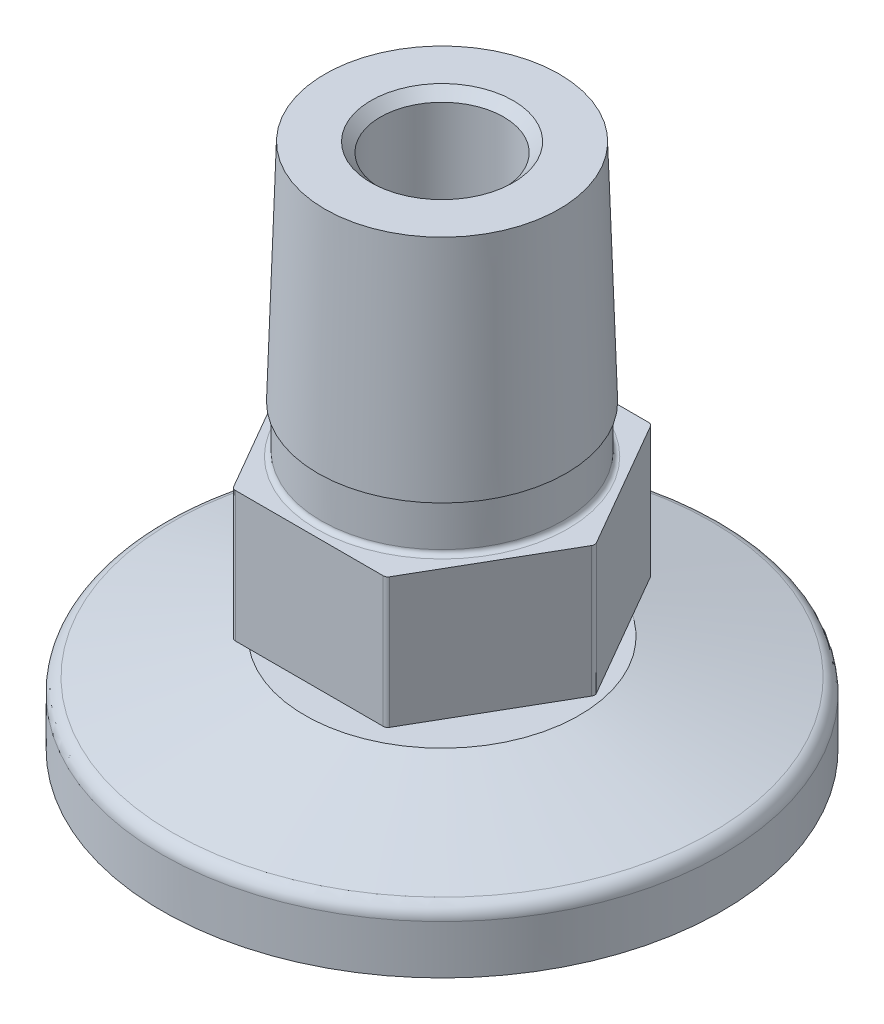
SolidWorks part; units mm, degrees
material "AISI 316 Annealed Stainless Steel Bar (SS)"
ref_plane "Front Plane" through (0, 0, 0) normal (0, 0, 1) x (1, 0, 0)
ref_plane "Top Plane" through (0, 0, 0) normal (0, 1, 0) x (1, 0, 0)
ref_plane "Right Plane" through (0, 0, 0) normal (1, 0, 0) x (0, 0, -1)
sketch "Sketch1" plane through (0, 0, 0) normal (1, 0, 0) x (0, 0, -1)
  line L0 (0, 0) -> (0, 5.25) construction
  line L1 (-15, 0) -> (-15, 3.2)
  line L2 (-15, 3.2) -> (-7.3493, 5.25)
  line L6 (0, 2.5) -> (-8.1, 2.5)
  line L7 (-8.1, 2.5) -> (-8.1, 0)
  line L8 (-8.1, 0) -> (-15, 0)
  line L9 (-7.3493, 5.25) -> (0, 5.25)
  line L10 (0, 5.25) -> (0, 2.5)
  dimension "D1" = 75
  dimension "D2" = 14.6986
  dimension "Flange ID" = 16.2
  dimension "Flange OD" = 30
  dimension "D5" = 3.2
  dimension "Flange Height" = 5.25
  dimension "D9" = 2.5
revolve "Flange" add sketch "Sketch1" angle 360 about L0
sketch "Sketch5" plane through (0, 2.5, 0) normal (0, -1, 0) x (1, 0, 0)
  circle A0 centre (0, 0) radius 4.445
  dimension "D1" = 8.89
extrude "Stub" add sketch "Sketch5" against normal offset from surface (4.104 mm away) 6.604 up to face at (0, 0, -8.1)
ref_plane "Plane1" through (0, -1.905, 0) normal (0, -1, 0) x (-1, 0, 0)
sketch "Sketch6" plane through (0, 6.604, 0) normal (0, 1, 0) x (1, 0, 0)
  line L1 (4.1061, 7.112) -> (-4.1061, 7.112)
  line L2 (-4.1061, 7.112) -> (-8.2122, 0)
  line L3 (-8.2122, 0) -> (-4.1061, -7.112)
  line L4 (-4.1061, -7.112) -> (4.1061, -7.112)
  line L5 (4.1061, -7.112) -> (8.2122, 0)
  line L6 (8.2122, 0) -> (4.1061, 7.112)
  circle A0 centre (0, 0) radius 7.112 construction
  dimension "D1" = 14.224
extrude "Hex" add sketch "Sketch6" along normal blind 6.985
sketch "Sketch7" plane through (0, 0, 0) normal (0, 0, 1) x (1, 0, 0)
  line L0 (-6.731, 13.589) -> (-6.2746, 28.194)
  line L1 (-8.2122, 13.589) -> (-4.1061, 13.589) construction
  line L2 (-6.2746, 28.194) -> (0, 28.194)
  line L3 (0, 28.194) -> (0, 13.589)
  line L4 (-4.1061, 13.589) -> (4.1061, 13.589) construction
  line L5 (0, 13.589) -> (-6.731, 13.589)
  line L6 (0, 0) -> (0, 39.0241) construction
  dimension "D1" = 14.605
  dimension "D3" = 13.462
  dimension "D4" = 1.79
revolve "Thread Body" add sketch "Sketch7" angle 360 about L6
cosmetic thread "Cosmetic Thread1"
sketch "Sketch8" plane through (0, 2.5, 0) normal (0, -1, 0) x (1, 0, 0)
  circle A0 centre (0, 0) radius 9.652
  dimension "D1" = 19.304
extrude "Centering Ring Boss" [suppressed] add sketch "Sketch8" along normal up to surface (2.5 mm away)
sketch "Sketch9" [suppressed] plane through (0, 0, 0) normal (0, 0, 1) x (1, 0, 0)
  line L0 (-6.477, 35.306) -> (-6.0327, 49.53)
  line L1 (-6.0327, 49.53) -> (0, 49.53)
  line L2 (0, 49.53) -> (0, 35.306)
  line L3 (6.477, 35.306) -> (-6.477, 35.306) construction
  line L4 (0, 35.306) -> (-6.477, 35.306)
  line L5 (0, 0) -> (0, 39.9227) construction
  dimension "D1" = 1.789
  dimension "D2" = 19.05
revolve "ThreadBody" add sketch "Sketch9" angle 360 about L5
cosmetic thread "Cosmetic Thread2" [suppressed]
sketch "Sketch11" plane through (0, 0, 0) normal (0, 0, 1) x (1, 0, 0)
  line L0 (-21.717, 13.589) -> (-21.717, 16.129)
  line L1 (-21.717, 16.129) -> (-6.477, 16.129)
  line L2 (-6.477, 16.129) -> (-6.477, 13.589)
  line L3 (-6.477, 13.589) -> (-21.717, 13.589)
  line L4 (0, 0) -> (0, 108.0919) construction
  line L5 (-15, 0) -> (15, 0) construction
  dimension "D1" = 2.54
  dimension "D2" = 12.954
  dimension "D3" = 15.24
  dimension "1.37" = 13.589
revolve "Cut-Revolve1" cut sketch "Sketch11" angle 360 about L4
sketch "Sketch10" [suppressed] plane through (0, 5.25, 0) normal (0, 1, 0) x (1, 0, 0)
  line L1 (6.3791, 11.049) -> (-6.3791, 11.049)
  line L2 (-6.3791, 11.049) -> (-12.7583, 0)
  line L3 (-12.7583, 0) -> (-6.3791, -11.049)
  line L4 (-6.3791, -11.049) -> (6.3791, -11.049)
  line L5 (6.3791, -11.049) -> (12.7583, 0)
  line L6 (12.7583, 0) -> (6.3791, 11.049)
  circle A0 centre (0, 0) radius 11.049 construction
  dimension "D1" = 22.098
extrude "Hex Body" [suppressed] add sketch "Sketch10" along normal up to surface (30.056 mm away)
sketch "Sketch3" plane through (0, 0, 0) normal (0, 1, 0) x (1, 0, 0)
  circle A0 centre (0, 0) radius 3.302
  dimension "Bore Dia" = 6.604
extrude "Center Bore" cut sketch "Sketch3" along normal through all
sketch "Sketch12" [suppressed] plane through (0, 0, 0) normal (0, 0, 1) x (1, 0, 0)
  line L0 (-5.334, 25.4) -> (-5.334, 5.25) construction
  line L1 (-5.334, 19.812) -> (-4.7625, 19.812)
  line L2 (-5.334, 19.812) -> (-5.334, 10.414)
  line L3 (-5.334, 10.414) -> (-4.7625, 10.414)
  line L4 (-4.7625, 19.812) -> (-4.7625, 10.414)
  line L5 (0, 0) -> (0, 21.9573) construction
  line L6 (5.334, 25.4) -> (-5.334, 25.4) construction
  line L7 (4.7625, 19.812) -> (4.7625, 10.414)
  line L8 (5.334, 10.414) -> (4.7625, 10.414)
  line L9 (5.334, 19.812) -> (5.334, 10.414)
  line L10 (5.334, 19.812) -> (4.7625, 19.812)
  dimension "D1" = 9.398
  dimension "D2" = 5.588
  dimension "D3" = 9.525
extrude "Grip Face" [suppressed] cut sketch "Sketch12" against normal through all both and the other way through all
sketch "Sketch13" [suppressed] plane through (0, 0, 0) normal (0, 0, 1) x (1, 0, 0)
  line L0 (15.875, 7.62) -> (20.955, 11.811)
  line L1 (20.955, 11.811) -> (20.955, 28.575)
  line L2 (0, 0) -> (0, 54.9571) construction
  line L3 (20.955, 28.575) -> (14.224, 28.575)
  line L4 (14.224, 2.5) -> (14.224, 49.784) construction
  line L5 (14.224, 28.575) -> (14.224, 7.62)
  line L7 (14.224, 7.62) -> (15.875, 7.62)
  line L8 (15.875, 7.62) -> (-15.875, 7.62) construction
  line L9 (-27.5, 0) -> (27.5, 0) construction
  line L10 (15.875, 6.3149) -> (15.875, 7.62) construction
  dimension "D1" = 41.91
  dimension "D2" = 28.575
  dimension "D3" = 11.811
revolve "Center Body" [suppressed] add sketch "Sketch13" angle 360 about L2
sketch "Sketch14" [suppressed] plane through (0, 0, 0) normal (0, 0, 1) x (1, 0, 0)
  line L0 (-20.955, 28.575) -> (-20.955, 11.811) construction
  line L1 (-20.955, 22.352) -> (-17.399, 22.352)
  line L2 (-20.955, 22.352) -> (-20.955, 7.62)
  line L3 (-20.955, 7.62) -> (-17.399, 7.62)
  line L4 (-17.399, 22.352) -> (-17.399, 7.62)
  line L5 (0, 0) -> (0, 23.4644) construction
  line L6 (-27.5, 0) -> (27.5, 0) construction
  line L7 (15.875, 7.62) -> (-15.875, 7.62) construction
  line L8 (17.399, 22.352) -> (17.399, 7.62)
  line L9 (20.955, 7.62) -> (17.399, 7.62)
  line L10 (20.955, 22.352) -> (20.955, 7.62)
  line L11 (20.955, 22.352) -> (17.399, 22.352)
  dimension "D1" = 34.798
  dimension "D2" = 22.352
extrude "Flat" [suppressed] cut sketch "Sketch14" against normal through all both and the other way through all
sketch "Sketch16" [suppressed] plane through (0, 0, 0) normal (0, 0, 1) x (1, 0, 0)
  line L0 (-13.6382, 13.589) -> (-13.6382, 6.096) construction
  line L1 (-10.922, 13.589) -> (-13.6382, 13.589)
  line L2 (-13.6382, 13.589) -> (-13.6382, 12.827)
  line L3 (-6.8191, 9.8425) -> (-9.8255, 9.8425) construction
  line L4 (-6.8191, 13.589) -> (-6.8191, 6.096) construction
  line L5 (0, 0) -> (0, 12.3026) construction
  line L6 (-13.6382, 12.827) -> (-10.922, 13.589)
  dimension "D1" = 5.969
revolve "Hex Chamfer1" [suppressed] cut sketch "Sketch16" angle 360 about L5
sketch "Sketch17" [suppressed] plane through (0, 0, 0) normal (0, 0, 1) x (1, 0, 0)
  line L0 (-13.6382, 12.827) -> (-13.6382, 6.096) construction
  line L1 (-13.6382, 6.731) -> (-13.6382, 6.096)
  line L2 (-13.6382, 6.096) -> (-10.668, 6.096)
  line L3 (-13.6382, 6.731) -> (-10.668, 6.096)
  line L4 (-10.668, 6.096) -> (10.668, 6.096) construction
  line L5 (0, 0) -> (0, 8.787) construction
  dimension "D2" = 7.62
revolve "Hex Chamfer2" [suppressed] cut sketch "Sketch17" angle 360 about L5
sketch "Sketch19" [suppressed] plane through (0, 0, 0) normal (0, 0, 1) x (1, 0, 0)
  line L0 (-23.7568, 25.527) -> (-23.7568, 10.668) construction
  line L1 (-23.7568, 15.875) -> (-23.7568, 10.668)
  line L2 (-23.7568, 10.668) -> (-19.05, 10.668)
  line L3 (-23.7568, 25.527) -> (-11.8784, 25.527) construction
  line L4 (-23.7568, 15.875) -> (-19.05, 10.668)
  line L5 (0, 0) -> (0, 19.136) construction
  dimension "D1" = 12.065
revolve "Hex Chamfer" [suppressed] cut sketch "Sketch19" angle 360 about L5
fillet "Fillet1" radius 0.254 6 edges at (8.2122, 10.0965, 0) (-8.2122, 10.0965, 0) (-4.1061, 10.0965, -7.112) (4.1061, 10.0965, -7.112) (4.1061, 10.0965, 7.112) (-4.1061, 10.0965, 7.112)
fillet "Fillet2" radius 0.762 1 edges at (0, 3.2, -15)
chamfer "Chamfer1" distance 0.508 angle 45 1 edges at (0, 28.194, 3.302)
fillet "Fillet3" radius 0.254 1 edges at (0, 13.589, -6.477)
chamfer "Chamfer2" [suppressed] distance 0.508 angle 45
